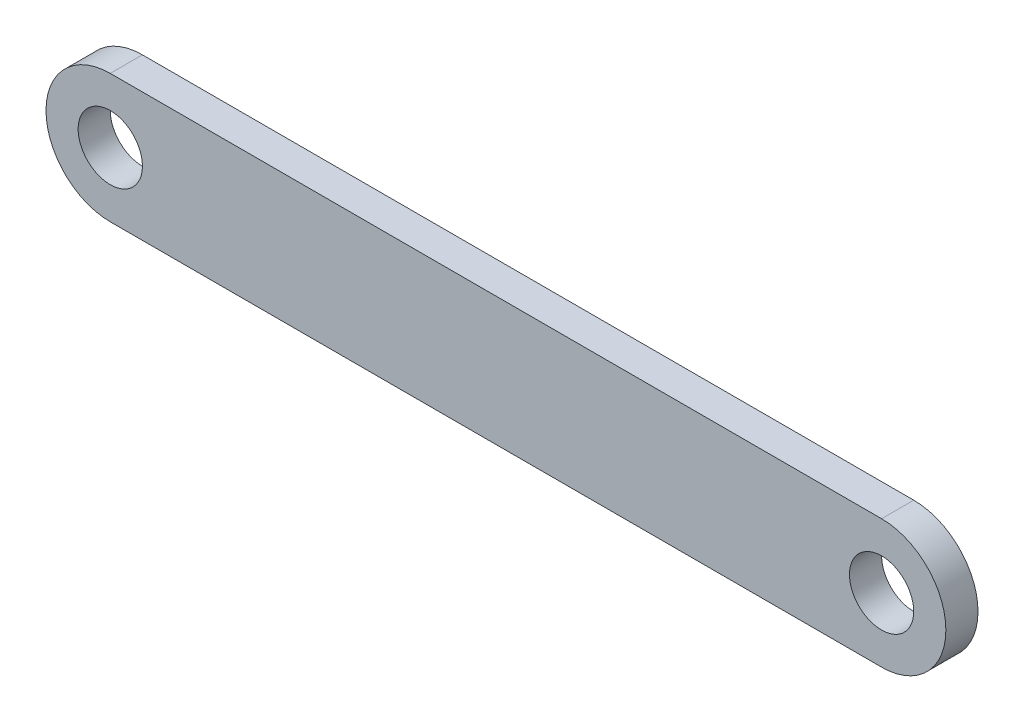
SolidWorks part; units mm, degrees
ref_plane "Front Plane" through (0, 0, 0) normal (0, 0, 1) x (1, 0, 0)
ref_plane "Top Plane" through (0, 0, 0) normal (0, 1, 0) x (1, 0, 0)
ref_plane "Right Plane" through (0, 0, 0) normal (1, 0, 0) x (0, 0, -1)
sketch "Sketch1" plane through (0, 0, 0) normal (0, 0, 1) x (1, 0, 0)
  line L0 (60, 0) -> (-60, 0) construction
  line L1 (60, -10) -> (-60, -10)
  line L2 (60, 10) -> (-60, 10)
  arc A0 (60, -10) -> (60, 10) centre (60, 0) ccw
  arc A1 (-60, 10) -> (-60, -10) centre (-60, 0) ccw
  circle A2 centre (-60, 0) radius 5
  circle A3 centre (60, 0) radius 5
  point P2 (0, 0)
  point P12 (0, 0)
  point P13 (0, 0)
  dimension "D1" = 120
  dimension "D2" = 20
extrude "Boss-Extrude2" add sketch "Sketch1" along normal blind 5
